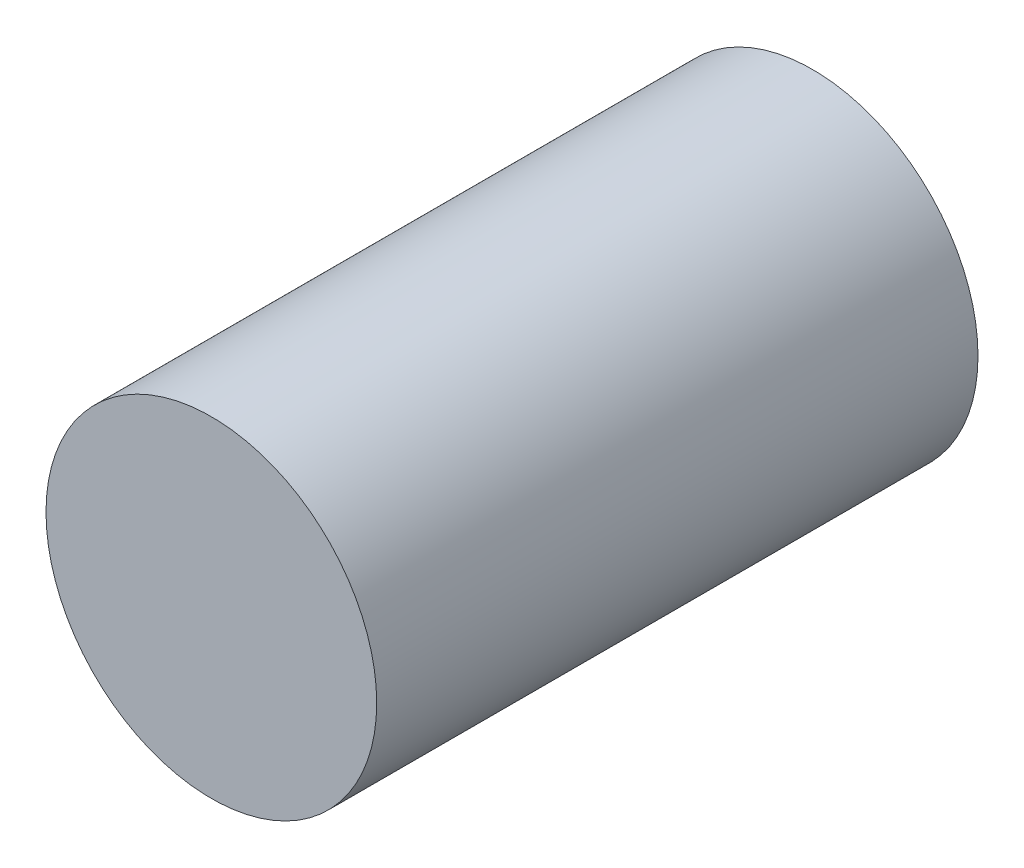
SolidWorks part; units mm, degrees
ref_plane "Front Plane" through (0, 0, 0) normal (0, 0, 1) x (1, 0, 0)
ref_plane "Top Plane" through (0, 0, 0) normal (0, 1, 0) x (1, 0, 0)
ref_plane "Right Plane" through (0, 0, 0) normal (1, 0, 0) x (0, 0, -1)
sketch "Sketch1" plane through (0, 0, 0) normal (0, 0, 1) x (1, 0, 0)
  circle A0 centre (0, 0) radius 1.65
extrude "Boss-Extrude1" add sketch "Sketch1" along normal blind 6 contours A0
